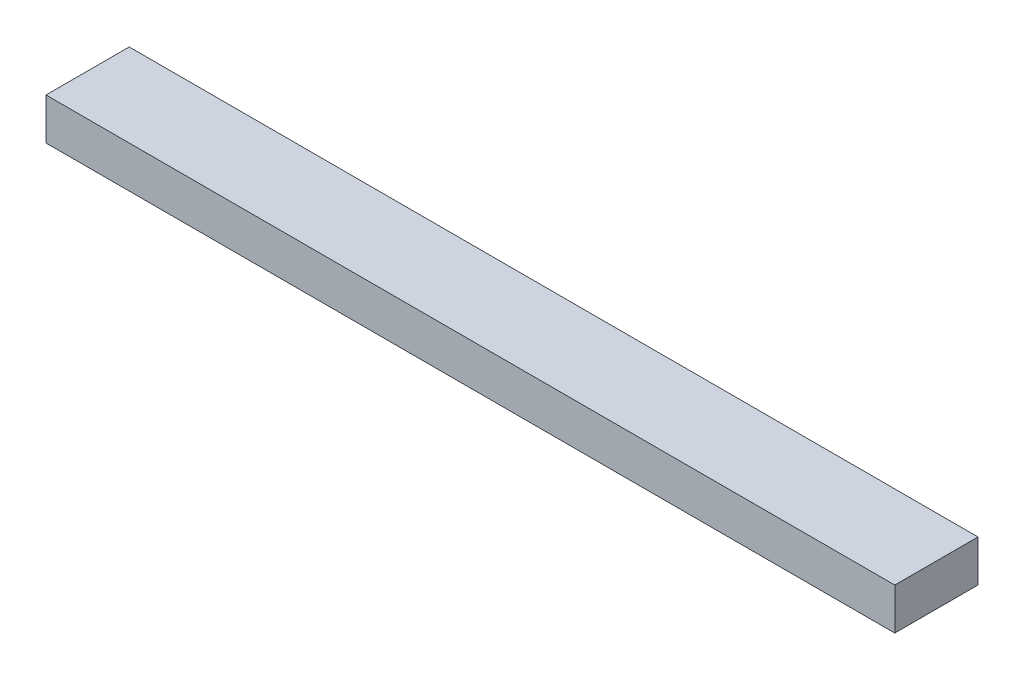
SolidWorks part; units mm, degrees
ref_plane "前视基准面" through (0, 0, 0) normal (0, 0, 1) x (1, 0, 0)
ref_plane "上视基准面" through (0, 0, 0) normal (0, 1, 0) x (1, 0, 0)
ref_plane "右视基准面" through (0, 0, 0) normal (1, 0, 0) x (0, 0, -1)
sketch "草图1" plane through (0, 0, 0) normal (0, 1, 0) x (1, 0, 0)
  line L0 (0, 0) -> (101.9873, 0)
  line L1 (101.9873, 0) -> (101.9873, -10)
  line L2 (101.9873, -10) -> (0, -10)
  line L3 (0, -10) -> (0, 0)
extrude "凸台-拉伸1" add sketch "草图1" along normal blind 5
